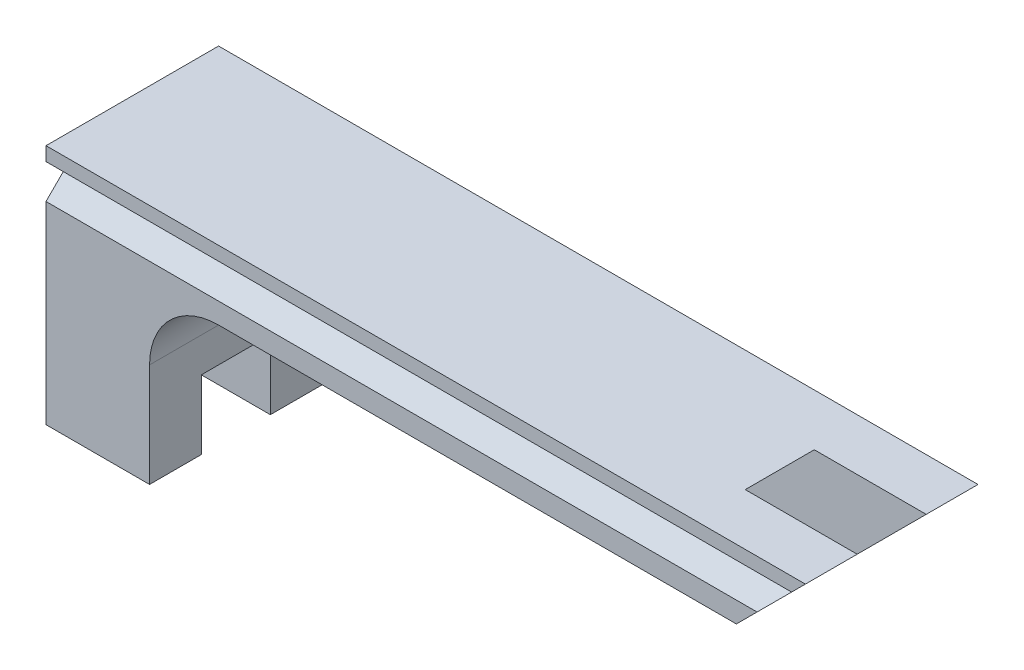
SolidWorks part; units mm, degrees
ref_plane "前视基准面" through (0, 0, 0) normal (0, 0, 1) x (1, 0, 0)
ref_plane "上视基准面" through (0, 0, 0) normal (0, 1, 0) x (1, 0, 0)
ref_plane "右视基准面" through (0, 0, 0) normal (1, 0, 0) x (0, 0, -1)
sketch "草图1" plane through (0, 0, 0) normal (0, 0, 1) x (1, 0, 0)
  line L1 (-110, 35) -> (110, 35)
  line L2 (-110, 35) -> (-110, -35)
  line L3 (-110, -35) -> (110, -35)
  line L4 (110, 35) -> (110, -35)
  line L5 (-110, 35) -> (110, -35) construction
  line L6 (-110, -35) -> (110, 35) construction
  point P0 (0, 0)
  dimension "D1" = 220
  dimension "D2" = 70
extrude "凸台-拉伸1" add sketch "草图1" along normal blind 30
sketch "草图2" plane through (0, 0, 30) normal (0, 0, 1) x (1, 0, 0)
  line L0 (-110, -35) -> (110, -35) construction
  line L1 (-80, -35) -> (110, -35)
  line L2 (-80, -35) -> (-80, 15)
  line L3 (-80, 15) -> (110, 15)
  line L4 (110, -35) -> (110, 15)
  line L5 (110, -35) -> (110, 35) construction
  line L6 (-110, 35) -> (-110, -35) construction
  line L7 (110, 35) -> (-110, 35) construction
  dimension "D1" = 30
  dimension "D2" = 20
extrude "切除-拉伸1" cut sketch "草图2" against normal blind 30
sketch "草图3" plane through (-80, 0, 0) normal (1, 0, 0) x (0, 0, -1)
  line L0 (0, -35) -> (-30, -35) construction
  line L1 (-5, -55) -> (-25, -55)
  line L2 (-5, -55) -> (-5, -15)
  line L3 (-5, -15) -> (-25, -15)
  line L4 (-25, -55) -> (-25, -15)
  line L5 (-5, -55) -> (-25, -15) construction
  line L6 (-5, -15) -> (-25, -55) construction
  point P0 (-15, -35)
  dimension "D1" = 20
  dimension "D2" = 20
extrude "切除-拉伸2" cut sketch "草图3" against normal blind 30
sketch "草图4" plane through (0, 0, 30) normal (0, 0, 1) x (1, 0, 0)
  line L0 (110, 35) -> (90, 15)
  line L1 (110, 15) -> (-80, 15) construction
  line L2 (90, 15) -> (110, 15)
  line L3 (110, 15) -> (110, 35)
  dimension "D1" = 45
extrude "切除-拉伸3" cut sketch "草图4" against normal blind 30
sketch "草图5" plane through (37.5, -37.5, 0) normal (0.7071, -0.7071, 0) x (0, 0, -1)
  line L0 (-30, 102.5305) -> (0, 102.5305) construction
  line L1 (-25, 132.5305) -> (-5, 132.5305)
  line L2 (-25, 132.5305) -> (-25, 72.5305)
  line L3 (-25, 72.5305) -> (-5, 72.5305)
  line L4 (-5, 132.5305) -> (-5, 72.5305)
  line L5 (-25, 132.5305) -> (-5, 72.5305) construction
  line L6 (-25, 72.5305) -> (-5, 132.5305) construction
  point P0 (-15, 102.5305)
  dimension "D1" = 20
  dimension "D2" = 30
extrude "切除-拉伸4" cut sketch "草图5" against normal blind 30
sketch "草图6" plane through (0, 35, 0) normal (0, 1, 0) x (1, 0, 0)
  line L4 (87.5736, -5) -> (67.5736, -5)
  line L5 (67.5736, -5) -> (67.5736, -25)
  line L6 (67.5736, -25) -> (87.5736, -25)
  line L7 (87.5736, -25) -> (87.5736, -5)
  line L8 (87.5736, -5) -> (67.5736, -5)
  line L9 (67.5736, -5) -> (67.5736, -25)
  line L10 (67.5736, -25) -> (87.5736, -25)
  line L11 (87.5736, -25) -> (87.5736, -5)
  dimension "D1" = 0
extrude "切除-拉伸5" cut sketch "草图6" against normal blind 30
sketch "草图7" plane through (67.5736, 0, 0) normal (1, 0, 0) x (0, 0, -1)
  line L4 (-5, 15) -> (-5, 35)
  line L5 (-5, 35) -> (-25, 35)
  line L6 (-25, 35) -> (-25, 15)
  line L7 (-25, 15) -> (-5, 15)
  line L8 (-5, 15) -> (-5, 35)
  line L9 (-5, 35) -> (-25, 35)
  line L10 (-25, 35) -> (-25, 15)
  line L11 (-25, 15) -> (-5, 15)
  dimension "D1" = 0
extrude "切除-拉伸6" cut sketch "草图7" against normal blind 10
fillet "圆角1" radius 20 1 edges at (-80, 15, 15)
sketch "草图8" plane through (0, 0, 25) normal (0, 0, -1) x (-1, 0, 0)
  line L0 (-57.5736, 15) -> (-77.5736, 35)
  line L1 (-110, 35) -> (-57.5736, 35) construction
  line L2 (-77.5736, 35) -> (-57.5736, 35)
  line L3 (-57.5736, 35) -> (-57.5736, 15)
  dimension "D1" = 45
extrude "凸台-拉伸2" add sketch "草图8" along normal blind 22
sketch "草图9" plane through (0, 0, 30) normal (0, 0, 1) x (1, 0, 0)
  line L6 (90, 15) -> (110, 35)
  line L7 (110, 35) -> (-110, 35)
  line L8 (-110, 35) -> (-110, -35)
  line L9 (-110, -35) -> (-80, -35)
  line L10 (-80, -35) -> (-80, -5)
  line L11 (-60, 15) -> (90, 15)
  line L12 (90, 15) -> (110, 35)
  line L13 (110, 35) -> (-110, 35)
  line L14 (-110, 35) -> (-110, -35)
  line L15 (-110, -35) -> (-80, -35)
  line L16 (-80, -35) -> (-80, -5)
  line L17 (-60, 15) -> (90, 15)
  arc A1 (-60, 15) -> (-80, -5) centre (-60, -5) ccw
  arc A2 (-60, 15) -> (-80, -5) centre (-60, -5) ccw
  dimension "D1" = 0
extrude "凸台-拉伸3" add sketch "草图9" along normal blind 10
sketch "草图10" plane through (0, 0, 0) normal (0, 0, -1) x (-1, 0, 0)
  line L6 (110, 35) -> (-110, 35)
  line L7 (-110, 35) -> (-90, 15)
  line L8 (-90, 15) -> (60, 15)
  line L9 (80, -5) -> (80, -35)
  line L10 (80, -35) -> (110, -35)
  line L11 (110, -35) -> (110, 35)
  line L12 (110, 35) -> (-110, 35)
  line L13 (-110, 35) -> (-90, 15)
  line L14 (-90, 15) -> (60, 15)
  line L15 (80, -5) -> (80, -35)
  line L16 (80, -35) -> (110, -35)
  line L17 (110, -35) -> (110, 35)
  arc A1 (80, -5) -> (60, 15) centre (60, -5) ccw
  arc A2 (80, -5) -> (60, 15) centre (60, -5) ccw
  dimension "D1" = 0
extrude "凸台-拉伸4" add sketch "草图10" along normal blind 10
sketch "草图11" plane through (0, 15, 0) normal (0, -1, 0) x (1, 0, 0)
  line L0 (-47.5, 15) -> (37.5, 15) construction
  line L1 (-47.5, 25) -> (37.5, 25)
  line L2 (-47.5, 5) -> (37.5, 5)
  line L3 (-60, 40) -> (90, 40) construction
  arc A0 (-47.5, 25) -> (-47.5, 5) centre (-47.5, 15) ccw
  arc A1 (37.5, 5) -> (37.5, 25) centre (37.5, 15) ccw
  point P2 (-5, 15)
  dimension "D1" = 10
  dimension "D2" = 25
  dimension "D3" = 85
  dimension "D4" = 5
extrude "切除-拉伸7" cut sketch "草图11" against normal blind 10
sketch "草图12" plane through (-110, 0, 0) normal (-1, 0, 0) x (0, 0, 1)
  line L0 (-10, 31) -> (-5, 26)
  line L1 (-10, -35) -> (-10, 35) construction
  line L2 (-5, 26) -> (-10, 21)
  line L3 (-10, 21) -> (-10, 31)
  line L4 (40, 31) -> (35, 26)
  line L5 (40, 35) -> (40, -35) construction
  line L6 (35, 26) -> (40, 21)
  line L7 (40, 21) -> (40, 31)
  line L8 (40, 35) -> (-10, 35) construction
  point P9 (0, 0)
  dimension "D1" = 5
  dimension "D2" = 5
  dimension "D3" = 10
  dimension "D4" = 4
extrude "切除-拉伸8" cut sketch "草图12" against normal blind 299
